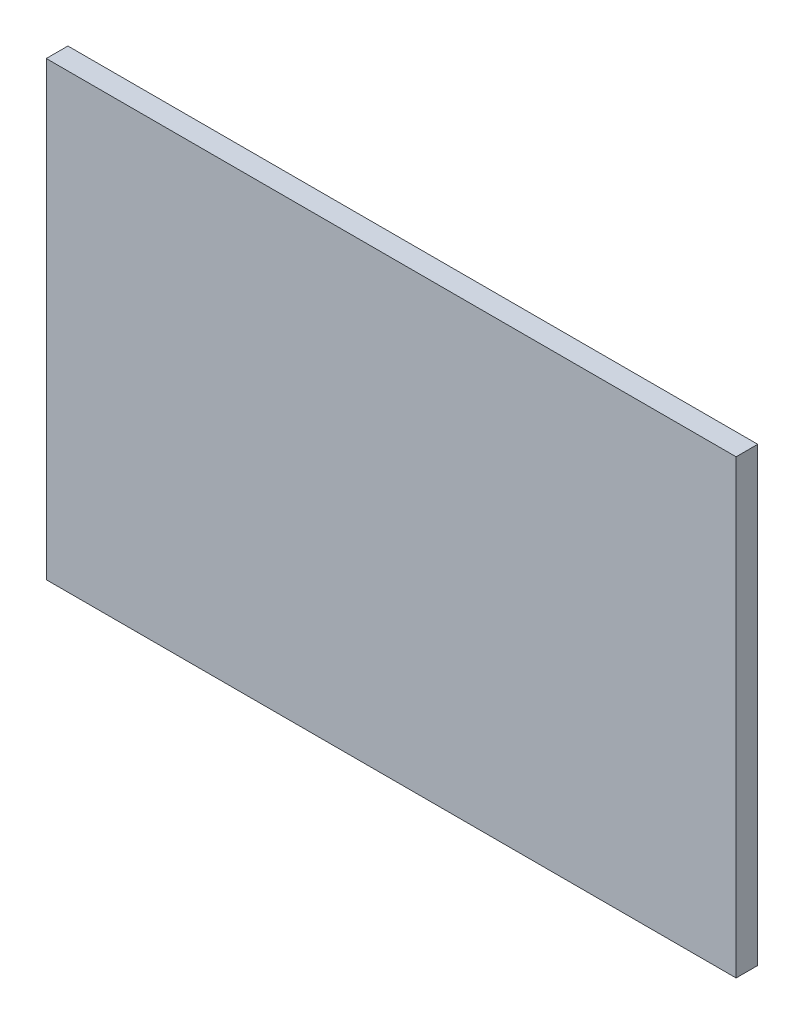
SolidWorks part; units mm, degrees
material "Гипс"
ref_plane "Спереди" through (0, 0, 0) normal (0, 0, 1) x (1, 0, 0)
ref_plane "Сверху" through (0, 0, 0) normal (0, 1, 0) x (1, 0, 0)
ref_plane "Справа" through (0, 0, 0) normal (1, 0, 0) x (0, 0, -1)
sketch "Эскиз1" plane through (0, 0, 0) normal (0, 0, 1) x (1, 0, 0)
  line L1 (-400, 0) -> (-1.5, 0)
  line L2 (-400, 0) -> (-400, -260.75)
  line L3 (-400, -260.75) -> (-1.5, -260.75)
  line L4 (-1.5, 0) -> (-1.5, -260.75)
extrude "Бобышка-Вытянуть1" add sketch "Эскиз1" against normal blind 12.5
